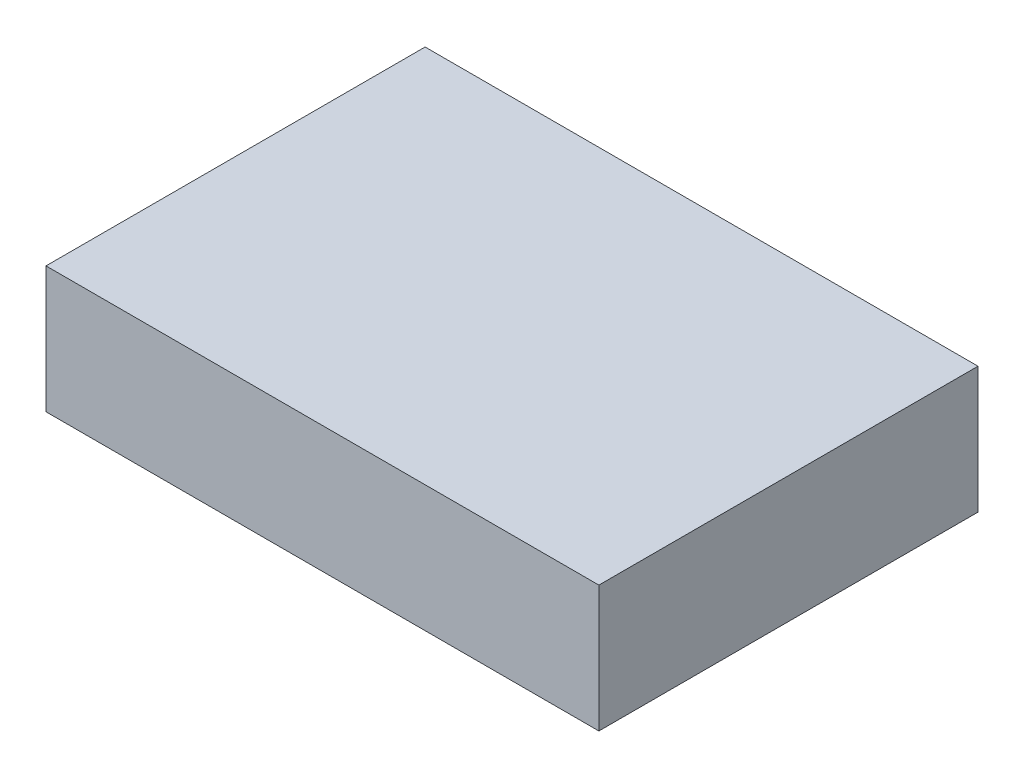
SolidWorks part; units mm, degrees
material "unobtainium"
ref_plane "Front Plane" through (0, 0, 0) normal (0, 0, 1) x (1, 0, 0)
ref_plane "Top Plane" through (0, 0, 0) normal (0, 1, 0) x (1, 0, 0)
ref_plane "Right Plane" through (0, 0, 0) normal (1, 0, 0) x (0, 0, -1)
sketch "Sketch1" plane through (0, 0, 0) normal (0, 1, 0) x (1, 0, 0)
  line L1 (-17.5, -12) -> (17.5, -12)
  line L2 (-17.5, -12) -> (-17.5, 12)
  line L3 (-17.5, 12) -> (17.5, 12)
  line L4 (17.5, -12) -> (17.5, 12)
  line L5 (-17.5, -12) -> (17.5, 12) construction
  line L6 (-17.5, 12) -> (17.5, -12) construction
  point P0 (0, 0)
  dimension "D1" = 24
  dimension "D2" = 35
extrude "Boss-Extrude1" add sketch "Sketch1" along normal blind 8
